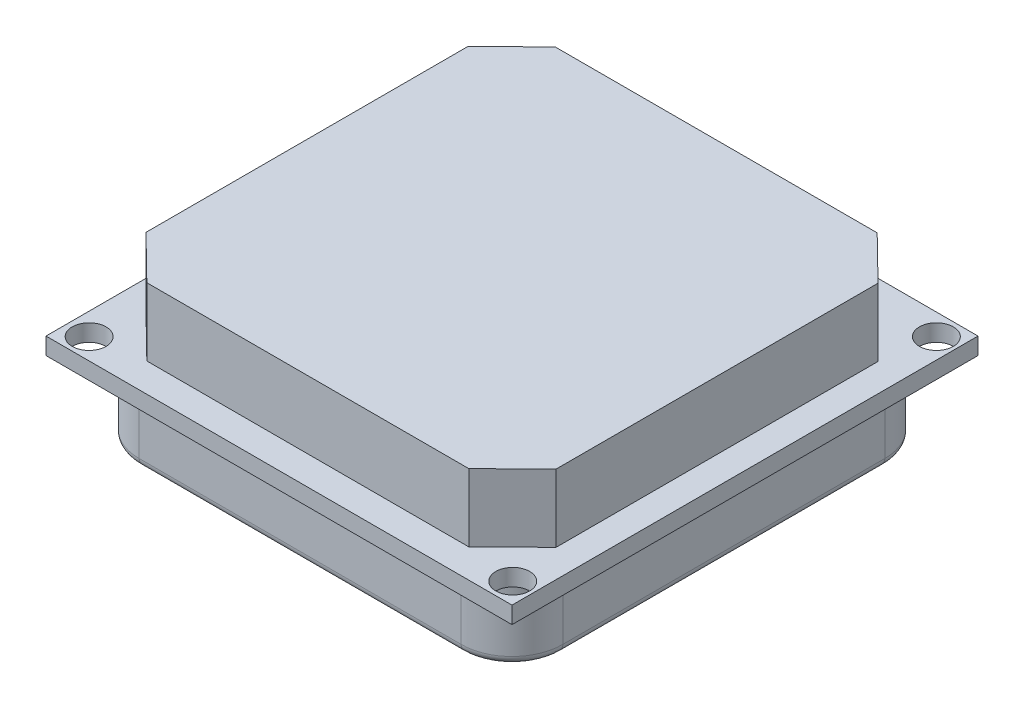
SolidWorks part; units mm, degrees
ref_plane "前视基准面" through (0, 0, 0) normal (0, 0, 1) x (1, 0, 0)
ref_plane "上视基准面" through (0, 0, 0) normal (0, 1, 0) x (1, 0, 0)
ref_plane "右视基准面" through (0, 0, 0) normal (1, 0, 0) x (0, 0, -1)
sketch "草图1" plane through (0, 0, 0) normal (0, 1, 0) x (1, 0, 0)
  line L0 (13.75, 13.75) -> (13.75, -13.75)
  line L1 (13.75, 13.75) -> (-13.75, 13.75)
  line L2 (13.75, -13.75) -> (-13.75, -13.75)
  line L3 (-13.75, 13.75) -> (-13.75, -13.75)
  line L4 (13.75, 13.75) -> (-13.75, -13.75) construction
  line L5 (13.75, -13.75) -> (-13.75, 13.75) construction
  point P1 (0, 0)
  dimension "D1" = 27.5
extrude "凸台-拉伸1" add sketch "草图1" along normal blind 1
sketch "草图2" plane through (0, 1, 0) normal (0, 1, 0) x (1, 0, 0)
  circle A0 centre (-12.448, 12.4921) radius 1
  circle A1 centre (12.552, 12.4921) radius 1
  circle A2 centre (12.552, -12.5079) radius 1
  circle A3 centre (-12.448, -12.5079) radius 1
  point P8 (0, 0)
  point P10 (-11.8935, -7.1077)
  dimension "D1" = 2
  dimension "D2" = 25
  dimension "D3" = 25
  dimension "D4" = 25
extrude "切除-拉伸1" cut sketch "草图2" against normal blind 1
sketch "草图3" plane through (0, 1, 0) normal (0, 1, 0) x (1, 0, 0)
  line L0 (-18.153, 0) -> (24.6455, 0) construction
  line L1 (-12.1, 9.5) -> (12.1, 9.5) construction
  line L2 (-12.1, 9.5) -> (-12.1, -9.5) construction
  line L3 (-12.1, -9.5) -> (12.1, -9.5) construction
  line L4 (12.1, 9.5) -> (12.1, -9.5) construction
  line L5 (-9.5, 12.05) -> (9.5, 12.05) construction
  line L6 (-9.5, 12.05) -> (-9.5, -12.05) construction
  line L7 (-9.5, -12.05) -> (9.5, -12.05) construction
  line L8 (9.5, 12.05) -> (9.5, -12.05) construction
  line L9 (0, 19.6915) -> (0, -21.3937) construction
  line L10 (-9.5, 12.05) -> (-12.1, 9.5)
  line L11 (-12.1, 9.5) -> (-12.1, -9.5)
  line L12 (-12.1, -9.5) -> (-9.5, -12.05)
  line L13 (-9.5, -12.05) -> (9.5, -12.05)
  line L14 (9.5, -12.05) -> (12.1, -9.5)
  line L15 (12.1, -9.5) -> (12.1, 9.5)
  line L16 (12.1, 9.5) -> (9.5, 12.05)
  line L17 (9.5, 12.05) -> (-9.5, 12.05)
  dimension "D1" = 24.1
  dimension "D2" = 24.2
  dimension "D3" = 19
  dimension "D4" = 19
extrude "凸台-拉伸2" add sketch "草图3" along normal blind 4
sketch "草图4" plane through (0, 0, 0) normal (0, -1, 0) x (1, 0, 0)
  line L0 (0, 17.8523) -> (0, -18.8197) construction
  line L1 (-12.5, 9.5) -> (12.5, 9.5) construction
  line L2 (-12.5, 9.5) -> (-12.5, -9.5) construction
  line L3 (-12.5, -9.5) -> (12.5, -9.5) construction
  line L4 (12.5, 9.5) -> (12.5, -9.5) construction
  line L5 (-9.5, 12.5) -> (9.5, 12.5) construction
  line L6 (-9.5, 12.5) -> (-9.5, -12.5) construction
  line L7 (-9.5, -12.5) -> (9.5, -12.5) construction
  line L8 (9.5, 12.5) -> (9.5, -12.5) construction
  line L9 (-21.0877, 0) -> (21.5542, 0) construction
  line L10 (-9.5, 12.5) -> (9.5, 12.5)
  line L11 (12.5, 9.5) -> (12.5, -9.5)
  line L12 (9.5, -12.5) -> (-9.5, -12.5)
  line L13 (-12.5, -9.5) -> (-12.5, 9.5)
  arc A0 (9.5, 12.5) -> (12.5, 9.5) centre (9.5, 9.5) cw
  arc A1 (12.5, -9.5) -> (9.5, -12.5) centre (9.5, -9.5) cw
  arc A2 (-9.5, -12.5) -> (-12.5, -9.5) centre (-9.5, -9.5) cw
  arc A3 (-12.5, 9.5) -> (-9.5, 12.5) centre (-9.5, 9.5) cw
  dimension "D1" = 25
  dimension "D2" = 25
  dimension "D3" = 19
  dimension "D4" = 19
extrude "凸台-拉伸3" add sketch "草图4" along normal blind 4.26
sketch "草图5" plane through (0, -4.26, 0) normal (0, -1, 0) x (1, 0, 0)
  line L0 (12.5, -9.5) -> (12.5, 9.5) construction
  line L2 (9.5, 12.5) -> (-9.5, 12.5) construction
  circle A0 centre (2.5, 0.5) radius 1.6
  dimension "D1" = 3.2
  dimension "D2" = 10
  dimension "D3" = 12
extrude "凸台-拉伸4" add sketch "草图5" along normal blind 0.3
fillet "圆角1" radius 0.5 8 edges at (-11.6213, -4.26, 11.6213) (0, -4.26, 12.5) (11.6213, -4.26, 11.6213) (12.5, -4.26, 0) (11.6213, -4.26, -11.6213) (-12.5, -4.26, 0) (-11.6213, -4.26, -11.6213) (0, -4.26, -12.5)
